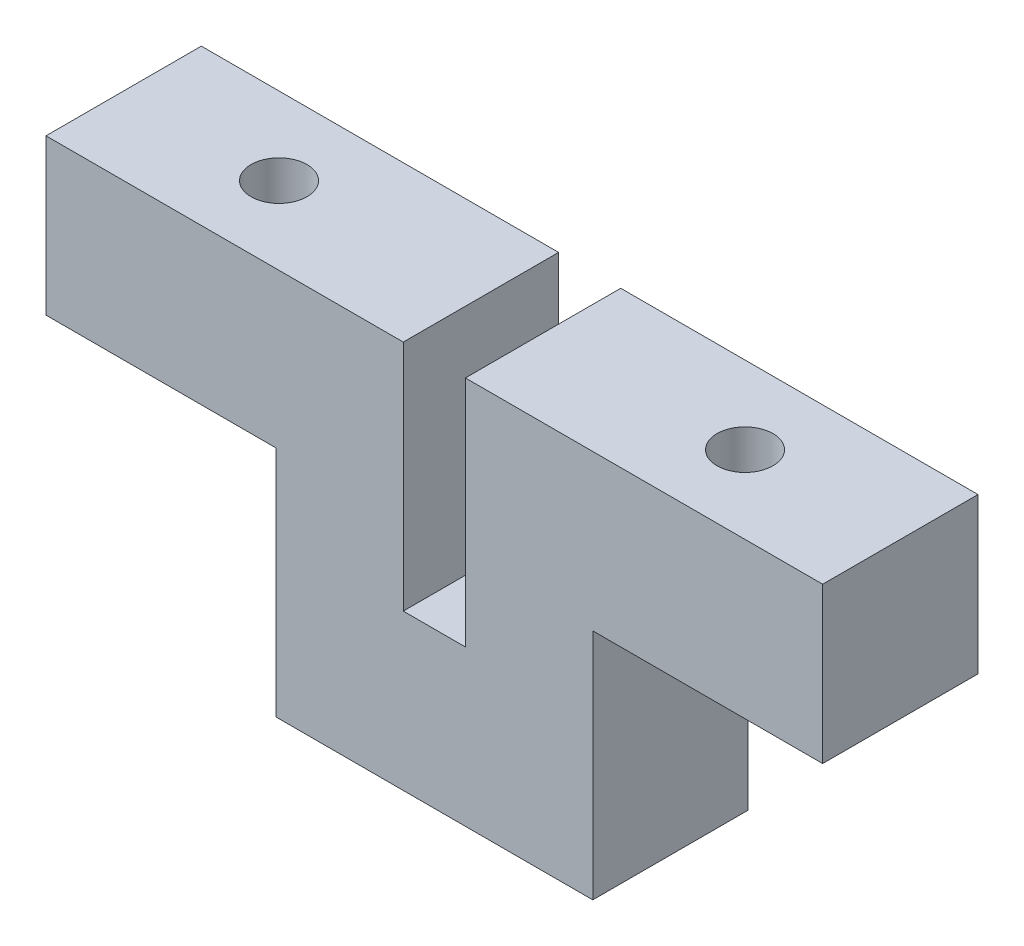
SolidWorks part; units mm, degrees
ref_plane "Front Plane" through (0, 0, 0) normal (0, 0, 1) x (1, 0, 0)
ref_plane "Top Plane" through (0, 0, 0) normal (0, 1, 0) x (1, 0, 0)
ref_plane "Right Plane" through (0, 0, 0) normal (1, 0, 0) x (0, 0, -1)
sketch "Sketch1" plane through (0, 0, 0) normal (0, 0, 1) x (1, 0, 0)
  line L0 (0, 0) -> (0, 25)
  line L1 (0, 25) -> (50, 25)
  line L2 (50, 25) -> (50, 0)
  line L3 (50, 0) -> (0, 0)
  line L4 (25, 25) -> (25, 0) construction
  dimension "D1" = 50
  dimension "D2" = 50
  dimension "D3" = 25
extrude "Boss-Extrude1" add sketch "Sketch1" along normal blind 10
sketch "Sketch2" plane through (0, 25, 0) normal (0, 1, 0) x (1, 0, 0)
  line L0 (10, -5) -> (40, -5) construction
  line L1 (25, -5) -> (25, 0) construction
  line L4 (50, 0) -> (0, 0) construction
  line L5 (50, -10) -> (0, -10) construction
  circle A0 centre (10, -5) radius 1.8
  circle A1 centre (40, -5) radius 1.8
  dimension "D3" = 30
  dimension "D4" = 3.6
  dimension "D5" = 3.6
  dimension "D1" = 5
  dimension "D2" = 5
extrude "Cut-Extrude1" cut sketch "Sketch2" against normal through all
sketch "Sketch3" plane through (0, 0, 10) normal (0, 0, 1) x (1, 0, 0)
  line L0 (50, 25) -> (0, 25) construction
  line L1 (23, 25) -> (27, 25)
  line L2 (23, 25) -> (23, 10)
  line L3 (23, 10) -> (27, 10)
  line L4 (27, 25) -> (27, 10)
  line L5 (0, 25) -> (23, 10) construction
  line L6 (27, 10) -> (50, 25) construction
  dimension "D1" = 4
  dimension "D2" = 15
extrude "Cut-Extrude2" cut sketch "Sketch3" against normal blind 10
sketch "Sketch6" plane through (0, 0, 10) normal (0, 0, 1) x (1, 0, 0)
  line L0 (0, 0) -> (50, 0) construction
  line L1 (0, 0) -> (14.8, 0)
  line L2 (0, 0) -> (0, 15)
  line L3 (0, 15) -> (14.8, 15)
  line L4 (14.8, 0) -> (14.8, 15)
  line L5 (35.2, 0) -> (50, 0)
  line L6 (35.2, 0) -> (35.2, 15)
  line L7 (35.2, 15) -> (50, 15)
  line L8 (50, 0) -> (50, 15)
  line L9 (50, 0) -> (50, 25) construction
  line L10 (23, 25) -> (0, 25) construction
  line L11 (50, 25) -> (27, 25) construction
  line L12 (11.8, 0) -> (11.8, 25) construction
  line L13 (38.2, 25) -> (38.2, 0) construction
  dimension "D1" = 10
  dimension "D2" = 10
  dimension "D3" = 3
  dimension "D4" = 3
extrude "Cut-Extrude3" cut sketch "Sketch6" against normal through all
equation "\"D2@Sketch6\"= \"D1@Sketch6\""
